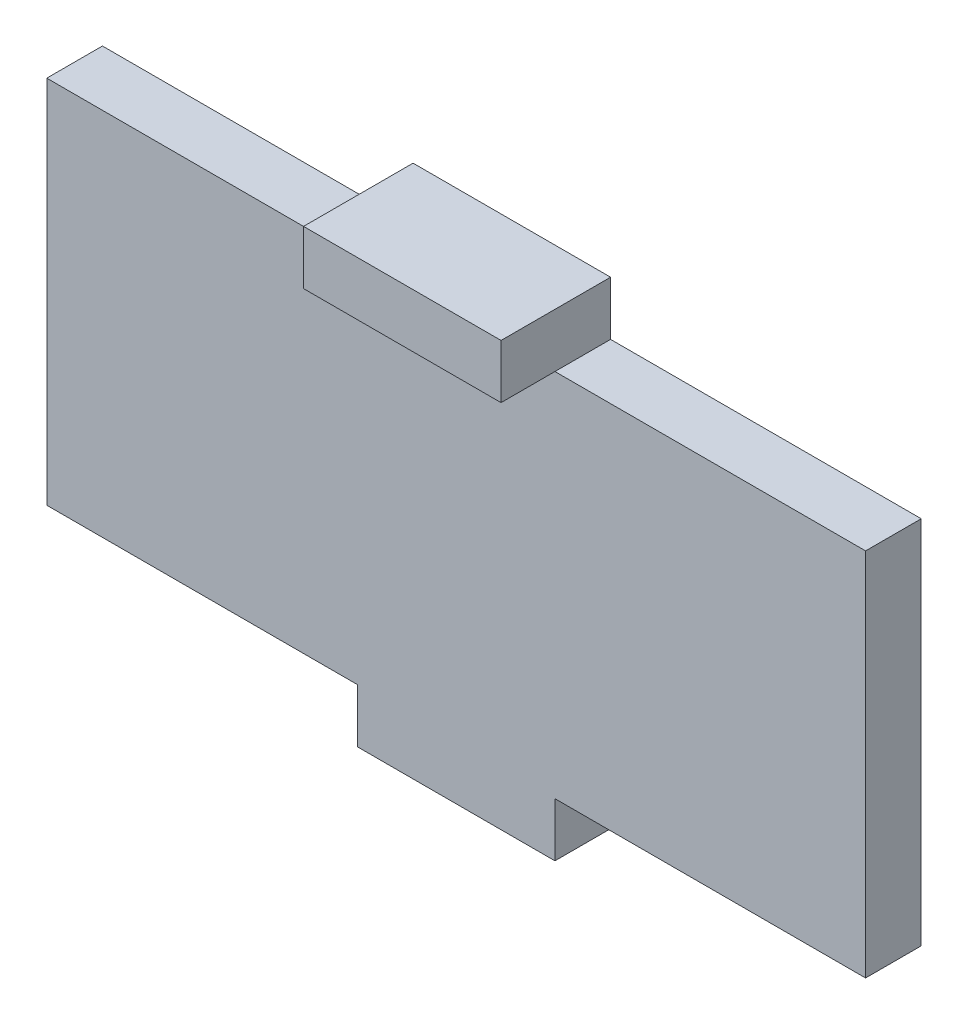
SolidWorks part; units mm, degrees
ref_plane "Front Plane" through (0, 0, 0) normal (0, 0, 1) x (1, 0, 0)
ref_plane "Top Plane" through (0, 0, 0) normal (0, 1, 0) x (1, 0, 0)
ref_plane "Right Plane" through (0, 0, 0) normal (1, 0, 0) x (0, 0, -1)
sketch "Sketch1" plane through (0, 0, 0) normal (0, 0, 1) x (1, 0, 0)
  line L0 (22.8, 20.6) -> (22.8, 23.6)
  line L1 (0, 0) -> (45.6, 0)
  line L2 (0, 0) -> (0, 20.6)
  line L3 (0, 20.6) -> (45.6, 20.6)
  line L4 (45.6, 0) -> (45.6, 20.6)
  line L5 (22.8, 23.6) -> (28.3, 23.6)
  line L6 (22.8, 0) -> (22.8, -3)
  line L7 (22.8, -3) -> (17.3, -3)
  line L9 (17.3, -3) -> (28.3, -3)
  line L10 (17.3, -3) -> (17.3, 23.6)
  line L11 (17.3, 23.6) -> (28.3, 23.6)
  line L12 (28.3, -3) -> (28.3, 23.6)
extrude "Boss-Extrude1" add sketch "Sketch1" along normal blind 1.1 contours L1 L10 L3 L2 | L11 L10 L3 L0 | L3 L12 L5 L0 | L1 L12 L3 L10 | L12 L1 L4 L3 | L9 L12 L1 L6 | L10 L7 L6 L1
sketch "Sketch2" plane through (0, 0, 1.1) normal (0, 0, 1) x (1, 0, 0)
  line L1 (17.3, 23.6) -> (28.3, 23.6)
  line L2 (17.3, 23.6) -> (17.3, 20.6)
  line L3 (17.3, 20.6) -> (28.3, 20.6)
  line L4 (28.3, 23.6) -> (28.3, 20.6)
extrude "Boss-Extrude2" add sketch "Sketch2" along normal blind 3
sketch "Sketch3" plane through (0, 0, 0) normal (0, 0, -1) x (-1, 0, 0)
  line L1 (-17.3, -3) -> (-28.3, -3)
  line L2 (-17.3, -3) -> (-17.3, 23.6)
  line L3 (-17.3, 23.6) -> (-28.3, 23.6)
  line L4 (-28.3, -3) -> (-28.3, 23.6)
  line L5 (-45.6, 0) -> (0, 0)
  line L6 (-45.6, 0) -> (-45.6, 20.6)
  line L7 (-45.6, 20.6) -> (0, 20.6)
  line L8 (0, 0) -> (0, 20.6)
  line M5 (-28.3, -3) -> (-17.3, -3)
  line M6 (-17.3, -3) -> (-17.3, 0)
  line M7 (-17.3, 0) -> (0, 0)
  line M8 (0, 0) -> (0, 20.6)
  line M9 (0, 20.6) -> (-17.3, 20.6)
  line M10 (-17.3, 20.6) -> (-17.3, 23.6)
  line M11 (-17.3, 23.6) -> (-28.3, 23.6)
  line M12 (-28.3, 23.6) -> (-28.3, 20.6)
  line M13 (-28.3, 20.6) -> (-45.6, 20.6)
  line M14 (-45.6, 20.6) -> (-45.6, 0)
  line M15 (-45.6, 0) -> (-28.3, 0)
  line M16 (-28.3, 0) -> (-28.3, -3)
extrude "Boss-Extrude3" add sketch "Sketch3" along normal blind 2 contours L4 M15 M13 M14 | L7 M12 M10 M11 | L7 L4 L5 L2 | L2 M7 M8 M9 | L5 M16 M5 M6
